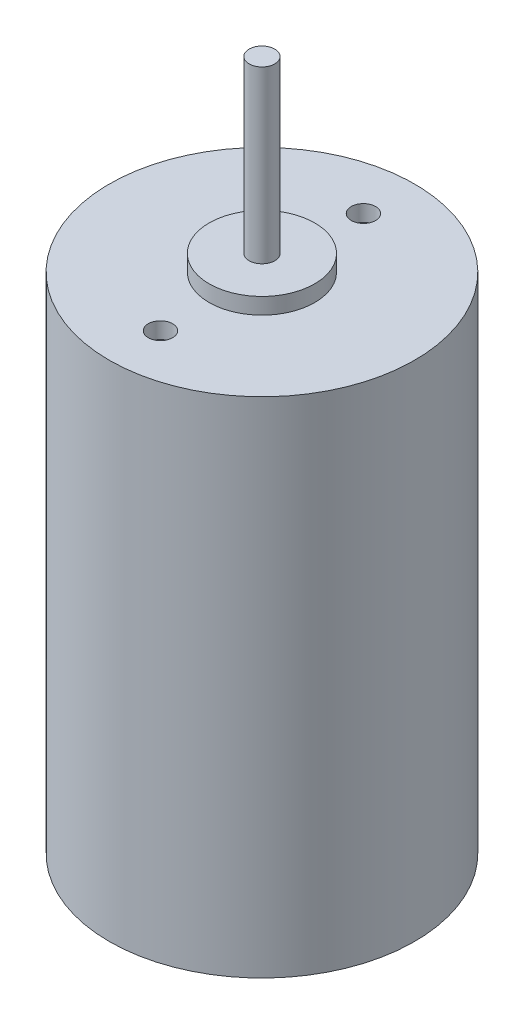
SolidWorks part; units mm, degrees
ref_plane "Front Plane" through (0, 0, 0) normal (0, 0, 1) x (1, 0, 0)
ref_plane "Top Plane" through (0, 0, 0) normal (0, 1, 0) x (1, 0, 0)
ref_plane "Right Plane" through (0, 0, 0) normal (1, 0, 0) x (0, 0, -1)
sketch "Sketch1" plane through (0, 0, 0) normal (0, 1, 0) x (1, 0, 0)
  circle A0 centre (0, 0) radius 18.8011
  dimension "D1" = 37.6022
extrude "Boss-Extrude1" add sketch "Sketch1" against normal blind 62
sketch "Sketch2" plane through (0, 0, 0) normal (0, 1, 0) x (1, 0, 0)
  circle A0 centre (0, 0) radius 1.58
  dimension "D1" = 3.16
extrude "Boss-Extrude2" add sketch "Sketch2" along normal blind 23
sketch "Sketch3" plane through (0, 0, 0) normal (0, 1, 0) x (1, 0, 0)
  circle A0 centre (0, 0) radius 12.5 construction
  circle A1 centre (0, 12.5) radius 1.5
  circle A2 centre (0, -12.5) radius 1.5
  dimension "D1" = 25
  dimension "D2" = 3
  dimension "D3" = 3
extrude "Cut-Extrude1" cut sketch "Sketch3" against normal blind 2
sketch "Sketch4" plane through (0, 0, 0) normal (0, 1, 0) x (1, 0, 0)
  circle A0 centre (0, 0) radius 6.5
  dimension "D1" = 13
extrude "Boss-Extrude3" add sketch "Sketch4" along normal blind 2
